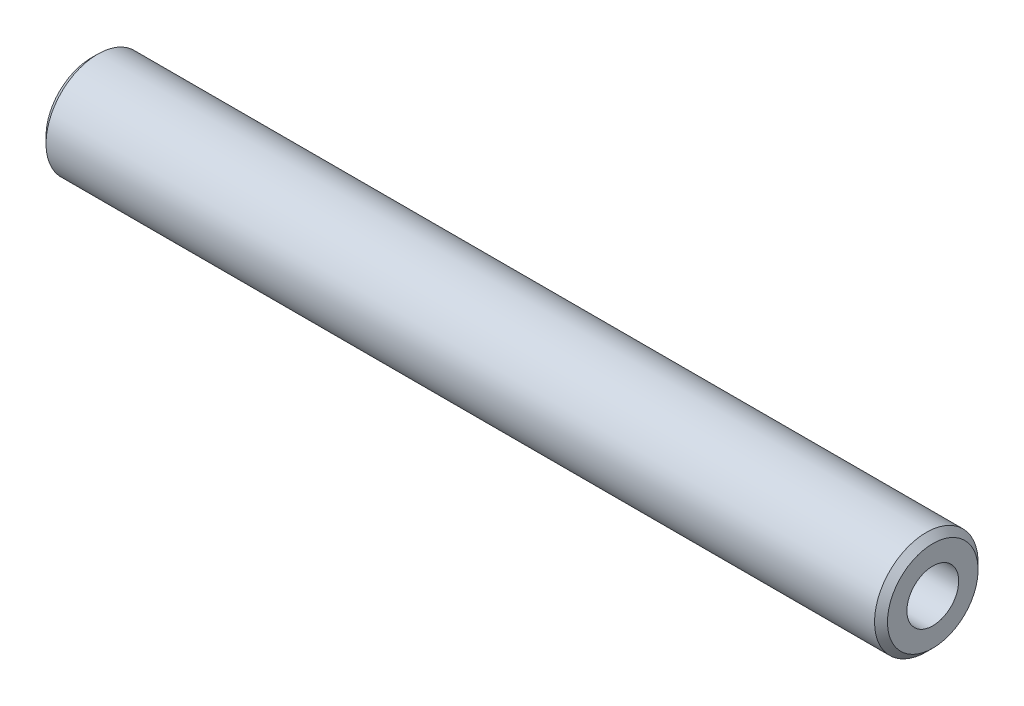
SolidWorks part; units mm, degrees
material "1.4301 (X5CrNi18-10)"
ref_plane "正面" through (0, 0, 0) normal (0, 0, 1) x (1, 0, 0)
ref_plane "平面" through (0, 0, 0) normal (0, 1, 0) x (1, 0, 0)
ref_plane "右側面" through (0, 0, 0) normal (1, 0, 0) x (0, 0, -1)
sketch "ｽｹｯﾁ1" plane through (0, 0, 0) normal (0, 0, 1) x (1, 0, 0)
  line L0 (0, 0) -> (21203.2319, 0) construction
  line L2 (-32.5, 0) -> (32.5, 0)
  line L3 (-32.5, 0) -> (-32.5, 4)
  line L4 (-32.5, 4) -> (32.5, 4)
  line L5 (32.5, 0) -> (32.5, 4)
  point P7 (0, 0)
  dimension "D1" = 8
  dimension "D2" = 65
revolve "回転1" add sketch "ｽｹｯﾁ1" angle 360 about L0
hole_wizard "M4x0.7 ねじ穴1" positions "3Dｽｹｯﾁ1" profile "ｽｹｯﾁ3" tap size "M4x0.7" standard "JIS"
sketch3d "3Dｽｹｯﾁ1"
  line L0 (32.5, 0, 0) -> (-32.5, 0, 0) construction
  point P0 (32.5, 0, 0)
  point P4 (-32.5, 0, 0)
sketch "ｽｹｯﾁ3" plane through (32.5, 0, 0) normal (0, 1, 0) x (0, 0, -1)
  line L0 (0, 0) -> (0, 12.4914)
  line L1 (0, 12.4914) -> (1.65, 11.5)
  line L2 (1.65, 11.5) -> (1.65, 8)
  line L3 (1.65, 8) -> (2, 8)
  line L4 (2, 8) -> (2, 0)
  line L5 (2, 0) -> (0, 0)
  line L10 (0, 12.4914) -> (-1.65, 11.5) construction
  line L11 (0, -6.35) -> (0, 107.95) construction
  dimension "ねじ下穴ﾄﾞﾘﾙ直径" = 3.3
  dimension "ねじ下穴ﾄﾞﾘﾙの深さ" = 11.5
  dimension "ねじ山の主要直径" = 4
  dimension "ねじ山の深さ" = 8
  dimension "ﾄﾞﾘﾙ角度" = 118
chamfer "面取り1" distance 0.5 angle 45 2 edges at (-32.5, 0, 4) (32.5, 0, 4)
